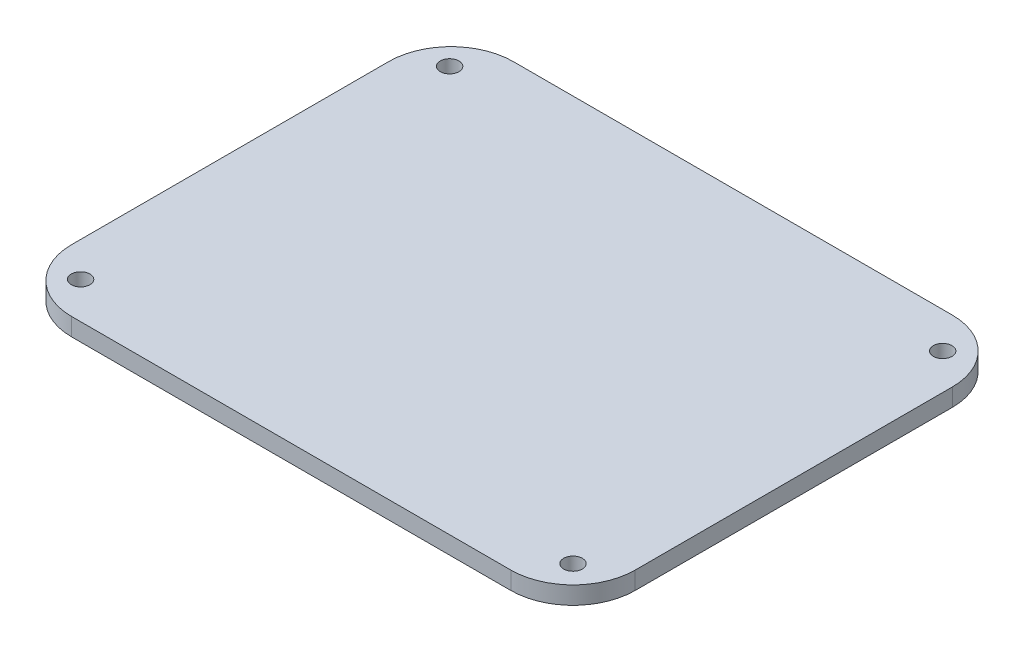
SolidWorks part; units mm, degrees
ref_plane "Front Plane" through (0, 0, 0) normal (0, 0, 1) x (1, 0, 0)
ref_plane "Top Plane" through (0, 0, 0) normal (0, 1, 0) x (1, 0, 0)
ref_plane "Right Plane" through (0, 0, 0) normal (1, 0, 0) x (0, 0, -1)
sketch "Sketch1" plane through (0, 0, 0) normal (0, 1, 0) x (1, 0, 0)
  line L1 (9, 0) -> (72.53, 0)
  line L2 (0, 9) -> (0, 54.88)
  line L3 (9, 63.88) -> (72.53, 63.88)
  line L4 (81.53, 9) -> (81.53, 54.88)
  arc A0 (9, 63.88) -> (0, 54.88) centre (9, 54.88) ccw
  arc A1 (0, 9) -> (9, 0) centre (9, 9) ccw
  arc A2 (72.53, 0) -> (81.53, 9) centre (72.53, 9) ccw
  arc A3 (81.53, 54.88) -> (72.53, 63.88) centre (72.53, 54.88) ccw
  circle A4 centre (5, 5.3) radius 1.35
  circle A5 centre (5, 58.68) radius 1.35
  circle A6 centre (76.33, 58.68) radius 1.35
  circle A7 centre (76.23, 5.3) radius 1.35
  point P9 (0, 0)
  point P12 (81.53, 0)
  point P15 (81.53, 63.88)
  point P24 (0, 0)
  dimension "D3" = 9
  dimension "D4" = 2.7
  dimension "D1" = 81.53
  dimension "D2" = 63.88
  dimension "D5" = 5.2
  dimension "D6" = 5.2
  dimension "D7" = 5.2
  dimension "D8" = 5
  dimension "D9" = 5.3
  dimension "D10" = 5
  dimension "D11" = 5.3
  dimension "D12" = 5.3
extrude "Boss-Extrude1" add sketch "Sketch1" along normal blind 2.56
